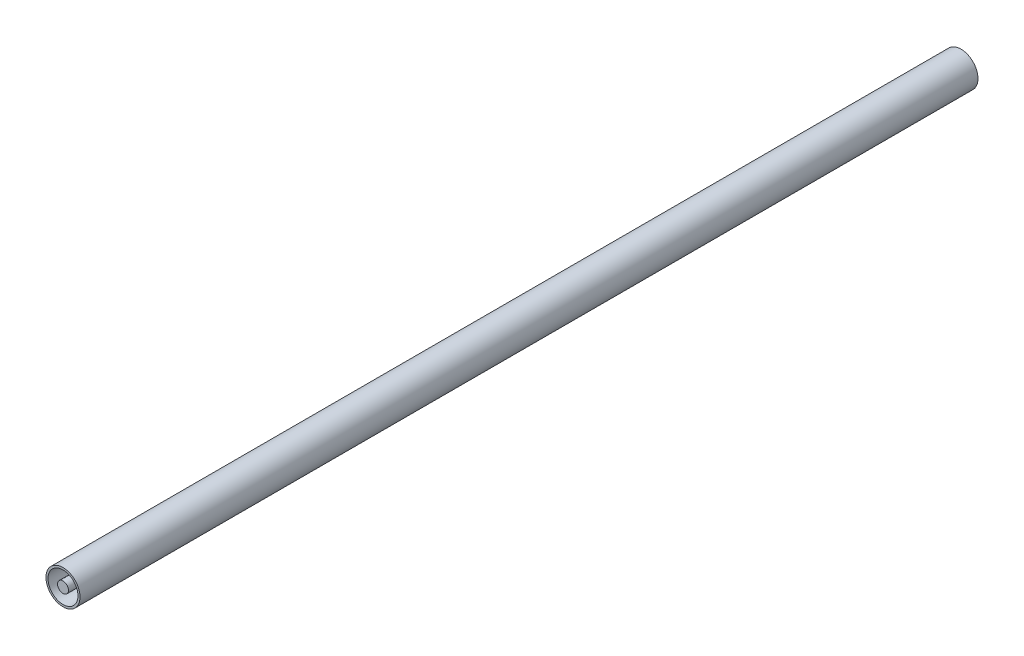
SolidWorks part; units mm, degrees
material "AISI Type 316L stainless steel"
ref_plane "Front Plane" through (0, 0, 0) normal (0, 0, 1) x (1, 0, 0)
ref_plane "Top Plane" through (0, 0, 0) normal (0, 1, 0) x (1, 0, 0)
ref_plane "Right Plane" through (0, 0, 0) normal (1, 0, 0) x (0, 0, -1)
sketch "Extrude sketch 1" plane through (0, 0, 0) normal (0, 0, 1) x (1, 0, 0)
  circle A0 centre (240, 0) radius 12.5
  circle A1 centre (240, 0) radius 11
  dimension "D1" = 22
  dimension "D2" = 25
extrude "Extrude 1" add sketch "Extrude sketch 1" along normal blind 659 from offset 350 separate body
sketch "Extrude sketch 2" plane through (0, 0, 0) normal (0, 0, 1) x (1, 0, 0)
  circle A0 centre (240, 0) radius 4
  dimension "D1" = 8
extrude "Extrude 2" add sketch "Extrude sketch 2" along normal blind 660 from offset 351 separate body
